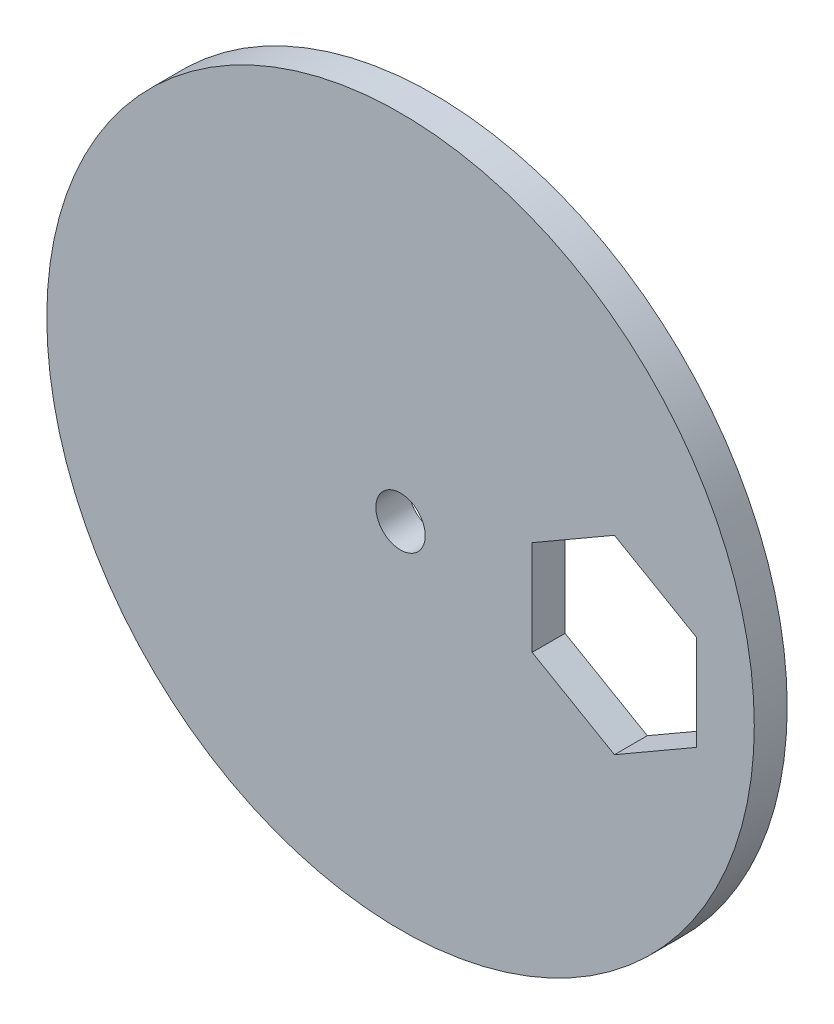
SolidWorks part; units mm, degrees
material "Acrylic (Medium-high impact)"
ref_plane "Front Plane" through (0, 0, 0) normal (0, 0, 1) x (1, 0, 0)
ref_plane "Top Plane" through (0, 0, 0) normal (0, 1, 0) x (1, 0, 0)
ref_plane "Right Plane" through (0, 0, 0) normal (1, 0, 0) x (0, 0, -1)
sketch "Sketch1" plane through (0, 0, 0) normal (0, 0, 1) x (1, 0, 0)
  line L0 (0, 21.5) -> (0, -21.5) construction
  line L2 (18, 2.8868) -> (13, 5.7735)
  line L3 (13, 5.7735) -> (8, 2.8868)
  line L4 (8, 2.8868) -> (8, -2.8868)
  line L5 (8, -2.8868) -> (13, -5.7735)
  line L6 (13, -5.7735) -> (18, -2.8868)
  line L7 (18, -2.8868) -> (18, 2.8868)
  circle A0 centre (0, 0) radius 21.5
  circle A2 centre (0, 0) radius 1.5
  circle A3 centre (13, 0) radius 5 construction
  dimension "D1" = 43
  dimension "D2" = 13
  dimension "D3" = 10
  dimension "D4" = 3
extrude "Boss-Extrude1" add sketch "Sketch1" along normal blind 2
